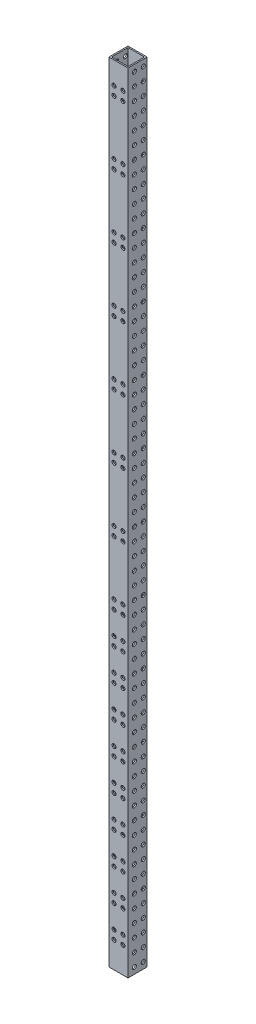
SolidWorks part; units mm, degrees
ref_plane "前视基准面" through (0, 0, 0) normal (0, 0, 1) x (1, 0, 0)
ref_plane "上视基准面" through (0, 0, 0) normal (0, 1, 0) x (1, 0, 0)
ref_plane "右视基准面" through (0, 0, 0) normal (1, 0, 0) x (0, 0, -1)
other "Configuration Table"
sketch "草图1" plane through (0, 0, 0) normal (0, 1, 0) x (1, 0, 0)
  line L1 (7.5, -7.5) -> (-7.5, -7.5)
  line L2 (7.5, -7.5) -> (7.5, 7.5)
  line L3 (7.5, 7.5) -> (-7.5, 7.5)
  line L4 (-7.5, -7.5) -> (-7.5, 7.5)
  line L5 (7.5, -7.5) -> (-7.5, 7.5) construction
  line L6 (7.5, 7.5) -> (-7.5, -7.5) construction
  line L11 (6.5, -6.5) -> (-6.5, -6.5)
  line L12 (6.5, -6.5) -> (6.5, 6.5)
  line L13 (6.5, 6.5) -> (-6.5, 6.5)
  line L14 (-6.5, -6.5) -> (-6.5, 6.5)
  line L15 (6.5, -6.5) -> (-6.5, 6.5) construction
  line L16 (6.5, 6.5) -> (-6.5, -6.5) construction
  point P0 (0, 0)
  point P6 (0, 0)
  dimension "D1" = 13
  dimension "D2" = 15
extrude "凸台-拉伸1" add sketch "草图1" along normal blind 620
sketch "草图3" plane through (0, 0, 7.5) normal (0, 0, 1) x (1, 0, 0)
  line L0 (0, 0) -> (0, 34.2901) construction
  line L1 (-7.5, 0) -> (7.5, 0) construction
  circle A0 centre (3.5, 245.5) radius 1.6
  circle A1 centre (-3.5, 245.5) radius 1.6
  circle A2 centre (-3.5, 252.5) radius 1.6
  circle A3 centre (3.5, 252.5) radius 1.6
  circle A4 centre (-3.5, 302.5) radius 1.6
  circle A5 centre (-3.5, 295.5) radius 1.6
  circle A6 centre (3.5, 295.5) radius 1.6
  circle A7 centre (3.5, 302.5) radius 1.6
  circle A8 centre (-3.5, 352.5) radius 1.6
  circle A9 centre (-3.5, 345.5) radius 1.6
  circle A10 centre (3.5, 345.5) radius 1.6
  circle A11 centre (3.5, 352.5) radius 1.6
  circle A12 centre (-3.5, 402.5) radius 1.6
  circle A13 centre (-3.5, 395.5) radius 1.6
  circle A14 centre (3.5, 395.5) radius 1.6
  circle A15 centre (3.5, 402.5) radius 1.6
  circle A16 centre (-3.5, 452.5) radius 1.6
  circle A17 centre (-3.5, 445.5) radius 1.6
  circle A18 centre (3.5, 445.5) radius 1.6
  circle A19 centre (3.5, 452.5) radius 1.6
  circle A20 centre (-3.5, 502.5) radius 1.6
  circle A21 centre (-3.5, 495.5) radius 1.6
  circle A22 centre (3.5, 495.5) radius 1.6
  circle A23 centre (3.5, 502.5) radius 1.6
  circle A24 centre (-3.5, 552.5) radius 1.6
  circle A25 centre (-3.5, 545.5) radius 1.6
  circle A26 centre (3.5, 545.5) radius 1.6
  circle A27 centre (3.5, 552.5) radius 1.6
  circle A28 centre (-3.5, 602.5) radius 1.6
  circle A29 centre (-3.5, 595.5) radius 1.6
  circle A30 centre (3.5, 595.5) radius 1.6
  circle A31 centre (3.5, 602.5) radius 1.6
  circle A32 centre (-3.5, 227.5) radius 1.6
  circle A33 centre (3.5, 227.5) radius 1.6
  circle A34 centre (-3.5, 220.5) radius 1.6
  circle A35 centre (3.5, 220.5) radius 1.6
  circle A36 centre (-3.5, 202.5) radius 1.6
  circle A37 centre (3.5, 202.5) radius 1.6
  circle A38 centre (-3.5, 195.5) radius 1.6
  circle A39 centre (3.5, 195.5) radius 1.6
  circle A40 centre (-3.5, 177.5) radius 1.6
  circle A41 centre (3.5, 177.5) radius 1.6
  circle A42 centre (-3.5, 170.5) radius 1.6
  circle A43 centre (3.5, 170.5) radius 1.6
  circle A44 centre (-3.5, 152.5) radius 1.6
  circle A45 centre (3.5, 152.5) radius 1.6
  circle A46 centre (-3.5, 145.5) radius 1.6
  circle A47 centre (3.5, 145.5) radius 1.6
  circle A48 centre (-3.5, 127.5) radius 1.6
  circle A49 centre (3.5, 127.5) radius 1.6
  circle A50 centre (-3.5, 120.5) radius 1.6
  circle A51 centre (3.5, 120.5) radius 1.6
  circle A52 centre (-3.5, 102.5) radius 1.6
  circle A53 centre (3.5, 102.5) radius 1.6
  circle A54 centre (-3.5, 95.5) radius 1.6
  circle A55 centre (3.5, 95.5) radius 1.6
  circle A56 centre (-3.5, 77.5) radius 1.6
  circle A57 centre (3.5, 77.5) radius 1.6
  circle A58 centre (-3.5, 70.5) radius 1.6
  circle A59 centre (3.5, 70.5) radius 1.6
  circle A60 centre (-3.5, 52.5) radius 1.6
  circle A61 centre (3.5, 52.5) radius 1.6
  circle A62 centre (-3.5, 45.5) radius 1.6
  circle A63 centre (3.5, 45.5) radius 1.6
  circle A64 centre (-3.5, 27.5) radius 1.6
  circle A65 centre (3.5, 27.5) radius 1.6
  circle A66 centre (-3.5, 20.5) radius 1.6
  circle A67 centre (3.5, 20.5) radius 1.6
  dimension "D1" = 3.2
  dimension "D2" = 3.5
  dimension "D3" = 245.5
  dimension "D4" = 2
  dimension "D5" = 8
  dimension "D6" = 10
extrude "切除-拉伸1" cut sketch "草图3" against normal up to surface (15 mm away) up to face at (0, 310, -7.5)
sketch "草图4" plane through (-7.5, 0, 0) normal (-1, 0, 0) x (0, 0, 1)
  line L0 (-34.7447, 297.1) -> (48.2892, 297.1) construction
  line L1 (-7.5, 0) -> (7.5, 0) construction
  line L2 (7.5, 620) -> (7.5, 0) construction
  circle A0 centre (2.5, 5) radius 1.6
  circle A1 centre (-4.5, 5) radius 1.6
  circle A2 centre (-4.5, 15) radius 1.6
  circle A3 centre (2.5, 15) radius 1.6
  circle A4 centre (-4.5, 25) radius 1.6
  circle A5 centre (2.5, 25) radius 1.6
  circle A6 centre (-4.5, 35) radius 1.6
  circle A7 centre (2.5, 35) radius 1.6
  circle A8 centre (-4.5, 45) radius 1.6
  circle A9 centre (2.5, 45) radius 1.6
  circle A10 centre (-4.5, 55) radius 1.6
  circle A11 centre (2.5, 55) radius 1.6
  circle A12 centre (-4.5, 65) radius 1.6
  circle A13 centre (2.5, 65) radius 1.6
  circle A14 centre (-4.5, 75) radius 1.6
  circle A15 centre (2.5, 75) radius 1.6
  circle A16 centre (-4.5, 85) radius 1.6
  circle A17 centre (2.5, 85) radius 1.6
  circle A18 centre (-4.5, 95) radius 1.6
  circle A19 centre (2.5, 95) radius 1.6
  circle A20 centre (-4.5, 105) radius 1.6
  circle A21 centre (2.5, 105) radius 1.6
  circle A22 centre (-4.5, 115) radius 1.6
  circle A23 centre (2.5, 115) radius 1.6
  circle A24 centre (-4.5, 125) radius 1.6
  circle A25 centre (2.5, 125) radius 1.6
  circle A26 centre (-4.5, 135) radius 1.6
  circle A27 centre (2.5, 135) radius 1.6
  circle A28 centre (-4.5, 145) radius 1.6
  circle A29 centre (2.5, 145) radius 1.6
  circle A30 centre (-4.5, 155) radius 1.6
  circle A31 centre (2.5, 155) radius 1.6
  circle A32 centre (-4.5, 165) radius 1.6
  circle A33 centre (2.5, 165) radius 1.6
  circle A34 centre (-4.5, 175) radius 1.6
  circle A35 centre (2.5, 175) radius 1.6
  circle A36 centre (-4.5, 185) radius 1.6
  circle A37 centre (2.5, 185) radius 1.6
  circle A38 centre (-4.5, 195) radius 1.6
  circle A39 centre (2.5, 195) radius 1.6
  circle A40 centre (-4.5, 205) radius 1.6
  circle A41 centre (2.5, 205) radius 1.6
  circle A42 centre (-4.5, 215) radius 1.6
  circle A43 centre (2.5, 215) radius 1.6
  circle A44 centre (-4.5, 225) radius 1.6
  circle A45 centre (2.5, 225) radius 1.6
  circle A46 centre (-4.5, 235) radius 1.6
  circle A47 centre (2.5, 235) radius 1.6
  circle A48 centre (-4.5, 245) radius 1.6
  circle A49 centre (2.5, 245) radius 1.6
  circle A50 centre (-4.5, 255) radius 1.6
  circle A51 centre (2.5, 255) radius 1.6
  circle A52 centre (-4.5, 265) radius 1.6
  circle A53 centre (2.5, 265) radius 1.6
  circle A54 centre (-4.5, 275) radius 1.6
  circle A55 centre (2.5, 275) radius 1.6
  circle A56 centre (-4.5, 285) radius 1.6
  circle A57 centre (2.5, 285) radius 1.6
  circle A58 centre (-4.5, 295) radius 1.6
  circle A59 centre (2.5, 295) radius 1.6
  circle A60 centre (-4.5, 305) radius 1.6
  circle A61 centre (2.5, 305) radius 1.6
  circle A62 centre (-4.5, 315) radius 1.6
  circle A63 centre (2.5, 315) radius 1.6
  circle A64 centre (-4.5, 325) radius 1.6
  circle A65 centre (2.5, 325) radius 1.6
  circle A66 centre (-4.5, 335) radius 1.6
  circle A67 centre (2.5, 335) radius 1.6
  circle A68 centre (-4.5, 345) radius 1.6
  circle A69 centre (2.5, 345) radius 1.6
  circle A70 centre (-4.5, 355) radius 1.6
  circle A71 centre (2.5, 355) radius 1.6
  circle A72 centre (-4.5, 365) radius 1.6
  circle A73 centre (2.5, 365) radius 1.6
  circle A74 centre (-4.5, 375) radius 1.6
  circle A75 centre (2.5, 375) radius 1.6
  circle A76 centre (-4.5, 385) radius 1.6
  circle A77 centre (2.5, 385) radius 1.6
  circle A78 centre (-4.5, 395) radius 1.6
  circle A79 centre (2.5, 395) radius 1.6
  circle A80 centre (-4.5, 405) radius 1.6
  circle A81 centre (2.5, 405) radius 1.6
  circle A82 centre (-4.5, 415) radius 1.6
  circle A83 centre (2.5, 415) radius 1.6
  circle A84 centre (-4.5, 425) radius 1.6
  circle A85 centre (2.5, 425) radius 1.6
  circle A86 centre (-4.5, 435) radius 1.6
  circle A87 centre (2.5, 435) radius 1.6
  circle A88 centre (-4.5, 445) radius 1.6
  circle A89 centre (2.5, 445) radius 1.6
  circle A90 centre (-4.5, 455) radius 1.6
  circle A91 centre (2.5, 455) radius 1.6
  circle A92 centre (-4.5, 465) radius 1.6
  circle A93 centre (2.5, 465) radius 1.6
  circle A94 centre (-4.5, 475) radius 1.6
  circle A95 centre (2.5, 475) radius 1.6
  circle A96 centre (-4.5, 485) radius 1.6
  circle A97 centre (2.5, 485) radius 1.6
  circle A98 centre (-4.5, 495) radius 1.6
  circle A99 centre (2.5, 495) radius 1.6
  circle A100 centre (-4.5, 505) radius 1.6
  circle A101 centre (2.5, 505) radius 1.6
  circle A102 centre (-4.5, 515) radius 1.6
  circle A103 centre (2.5, 515) radius 1.6
  circle A104 centre (-4.5, 525) radius 1.6
  circle A105 centre (2.5, 525) radius 1.6
  circle A106 centre (-4.5, 535) radius 1.6
  circle A107 centre (2.5, 535) radius 1.6
  circle A108 centre (-4.5, 545) radius 1.6
  circle A109 centre (2.5, 545) radius 1.6
  circle A110 centre (-4.5, 555) radius 1.6
  circle A111 centre (2.5, 555) radius 1.6
  circle A112 centre (-4.5, 565) radius 1.6
  circle A113 centre (2.5, 565) radius 1.6
  circle A114 centre (-4.5, 575) radius 1.6
  circle A115 centre (2.5, 575) radius 1.6
  circle A116 centre (-4.5, 585) radius 1.6
  circle A117 centre (2.5, 585) radius 1.6
  circle A118 centre (-4.5, 595) radius 1.6
  circle A119 centre (2.5, 595) radius 1.6
  circle A120 centre (-4.5, 605) radius 1.6
  circle A121 centre (2.5, 605) radius 1.6
  circle A122 centre (-4.5, 615) radius 1.6
  circle A123 centre (2.5, 615) radius 1.6
  dimension "D1" = 3.2
  dimension "D2" = 5
  dimension "D3" = 5
  dimension "D4" = 0
  dimension "D5" = 7
  dimension "D6" = 62
extrude "切除-拉伸2" cut sketch "草图4" against normal up to surface (15 mm away) up to face at (7.5, 310, 0)
